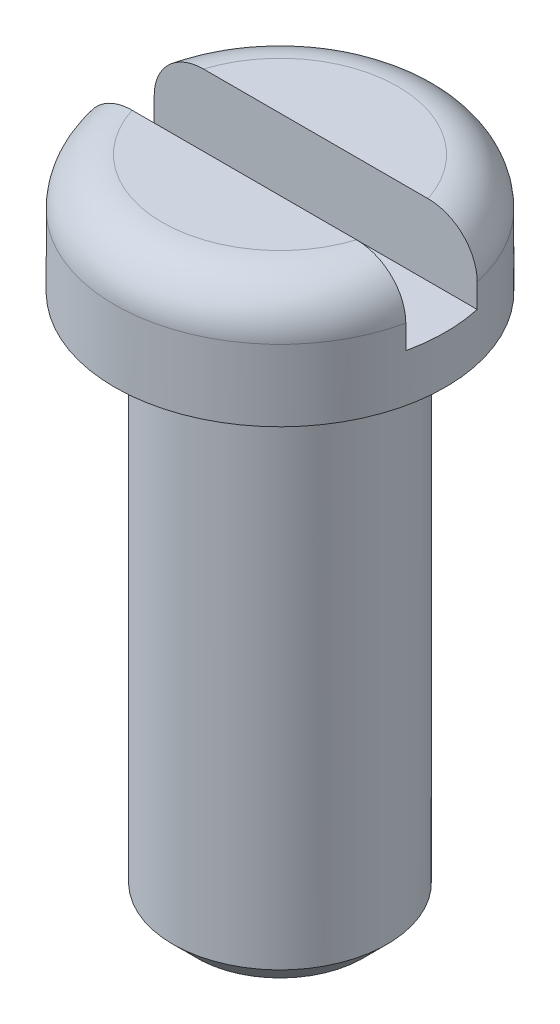
SolidWorks part; units mm, degrees
ref_plane "Спереди" through (0, 0, 0) normal (0, 0, 1) x (1, 0, 0)
ref_plane "Сверху" through (0, 0, 0) normal (0, 1, 0) x (1, 0, 0)
ref_plane "Справа" through (0, 0, 0) normal (1, 0, 0) x (0, 0, -1)
sketch "Эскиз1" plane through (0, 0, 0) normal (0, 1, 0) x (1, 0, 0)
  circle A0 centre (0, 0) radius 1.39
  dimension "D1" = 2.78
extrude "Бобышка-Вытянуть1" add sketch "Эскиз1" along normal blind 1
sketch "Эскиз2" plane through (0, 1, 0) normal (0, 1, 0) x (1, 0, 0)
  line L0 (-1.39, 0) -> (1.39, 0) construction
  line L1 (-1.39, 0.3) -> (1.39, 0.3)
  line L2 (-1.39, -0.3) -> (1.39, -0.3)
  line L3 (-1.39, 0.3) -> (-1.39, -0.3)
  line L4 (1.39, 0.3) -> (1.39, -0.3)
  circle A0 centre (0, 0) radius 1.39 construction
  dimension "D1" = 0.3
  dimension "D2" = 0.3
extrude "Вырез-Вытянуть1" cut sketch "Эскиз2" against normal blind 0.6
fillet "Скругление2" radius 0.4 2 edges at (0, 1, 1.39) (0, 1, -1.39)
sketch "Эскиз3" plane through (0, 0, 0) normal (0, -1, 0) x (1, 0, 0)
  circle A0 centre (0, 0) radius 0.9
  dimension "D1" = 1.8
extrude "Бобышка-Вытянуть2" add sketch "Эскиз3" along normal blind 4.5
chamfer "Фаска1" distance 0.2 angle 45 1 edges at (0, -4.5, -0.9)
